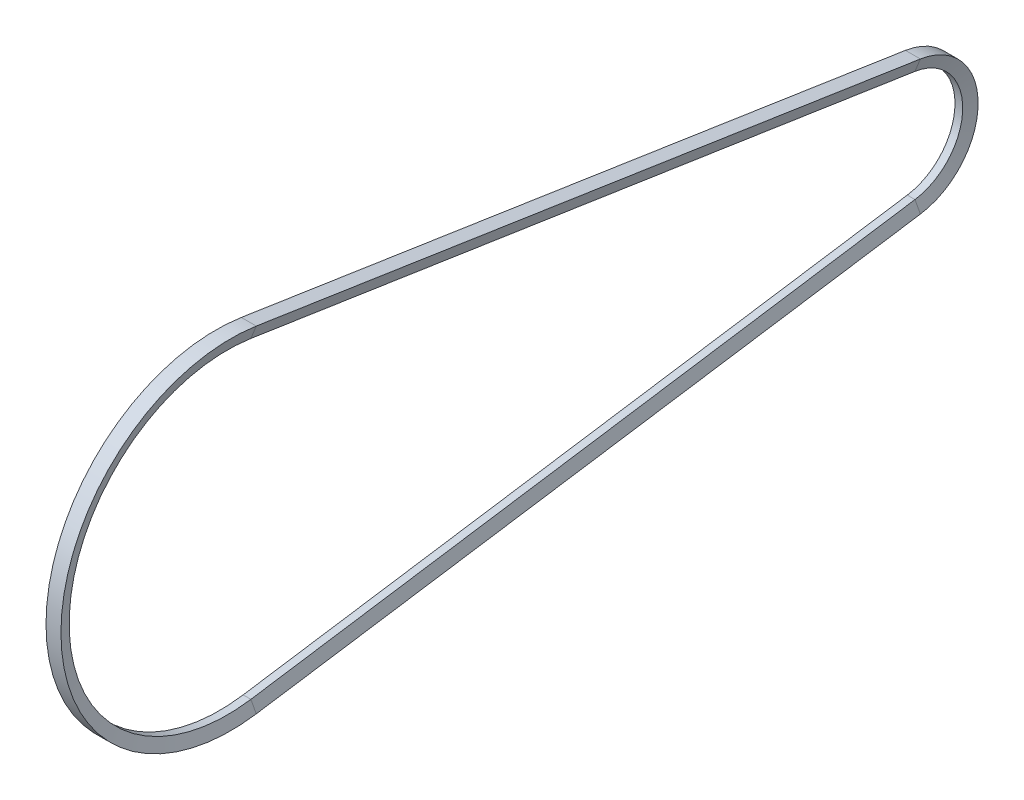
SolidWorks part; units mm, degrees
ref_plane "前视基准面" through (0, 0, 0) normal (0, 0, 1) x (1, 0, 0)
ref_plane "上视基准面" through (0, 0, 0) normal (0, 1, 0) x (1, 0, 0)
ref_plane "右视基准面" through (0, 0, 0) normal (1, 0, 0) x (0, 0, -1)
sketch "草图1" plane through (0, 0, 0) normal (1, 0, 0) x (0, 0, -1)
  line L0 (18.75, 123.5857) -> (507.5, 49.4343)
  line L1 (18.75, -123.5857) -> (507.5, -49.4343)
  line L2 (0, 0) -> (500, 0) construction
  arc A0 (18.75, 123.5857) -> (18.75, -123.5857) centre (0, 0) ccw
  arc A1 (507.5, -49.4343) -> (507.5, 49.4343) centre (500, 0) ccw
  dimension "D1" = 125
  dimension "D2" = 50
  dimension "D3" = 500
sketch "草图2" plane through (0, 0, 0) normal (0, 0, 1) x (1, 0, 0)
  line L0 (-5.5, 125) -> (5.5, 125)
  line L1 (5.5, 125) -> (2.8401, 116.3)
  line L2 (2.8401, 116.3) -> (-2.8401, 116.3)
  line L3 (-2.8401, 116.3) -> (-5.5, 125)
  line L4 (0, 116.3) -> (0, 125) construction
  line L5 (0, -125) -> (0, 125) construction
  dimension "D1" = 11
  dimension "D2" = 8.7
  dimension "D3" = 34
sweep "扫描1" add profiles "草图2" path "草图1"
equation "\"D3@草图1\" = \"D1@距离1@实心轮_辐板轮.Assembly\""
equation "\"D1@草图2\" = \"bd@草图1@小带轮_实心轮.Part\" "
equation "\"D2@草图2\" = \"hf@草图1@大带轮_辐板轮.Part\" "
equation "\"D3@草图2\" = \"槽轮角@草图1@大带轮_辐板轮.Part\" "
equation "\"D2@草图1\" = \"dd@草图1@小带轮_实心轮.Part\"/2"
equation "\"D1@草图1\" = \"dd@草图1@大带轮_辐板轮.Part\" /2"
